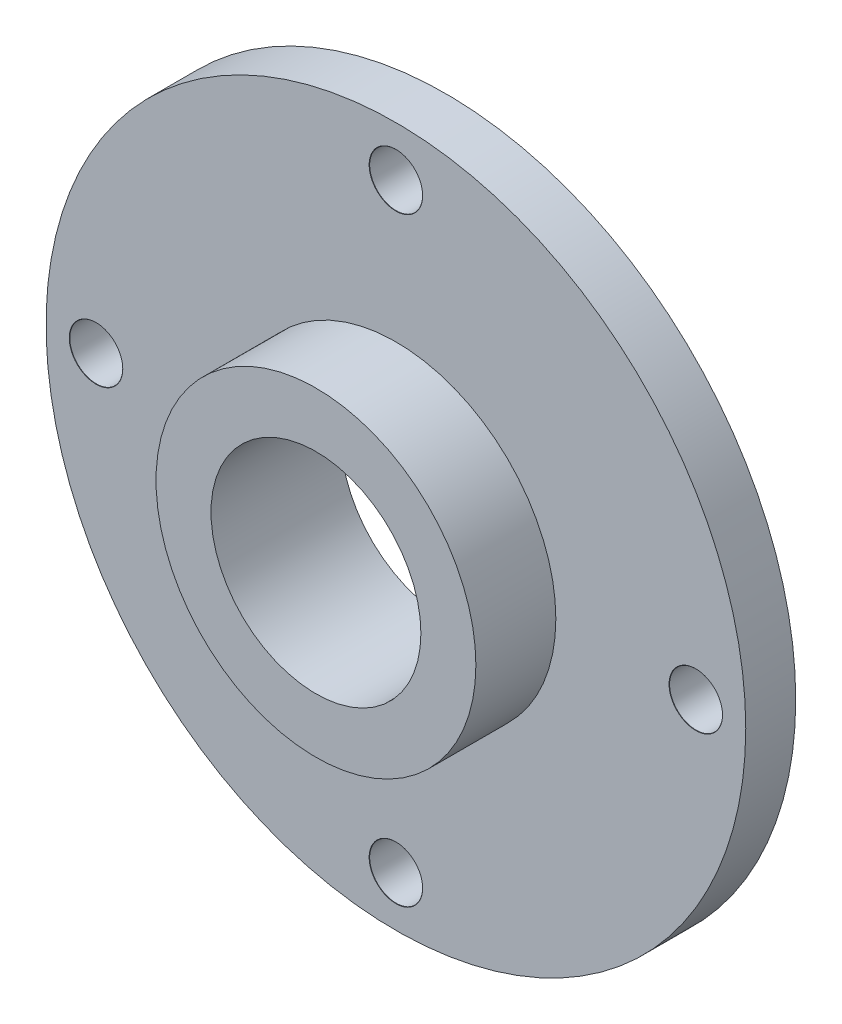
SolidWorks part; units mm, degrees
ref_plane "Front Plane" through (0, 0, 0) normal (0, 0, 1) x (1, 0, 0)
ref_plane "Top Plane" through (0, 0, 0) normal (0, 1, 0) x (1, 0, 0)
ref_plane "Right Plane" through (0, 0, 0) normal (1, 0, 0) x (0, 0, -1)
sketch "Sketch1" plane through (0, 0, 0) normal (0, 0, 1) x (1, 0, 0)
  circle A0 centre (0, 0) radius 35
  circle A1 centre (0, 0) radius 10.5
  dimension "D1" = 70
  dimension "D2" = 21
extrude "Boss-Extrude1" add sketch "Sketch1" along normal blind 5
sketch "Sketch2" plane through (0, 0, 5) normal (0, 0, 1) x (1, 0, 0)
  point P0 (0, 30)
  dimension "D1" = 30
hole_wizard "M5 Clearance Hole1" positions "Sketch2" profile "Sketch3" hole size "M5" standard "ISO" end condition through all
sketch "Sketch3" plane through (0, 30, 5) normal (1, 0, 0) x (0, -1, 0)
  line L0 (0, 0) -> (0, 5)
  line L1 (0, 5) -> (2.65, 5)
  line L2 (2.65, 5) -> (2.65, 0.025)
  line L3 (2.65, 0.025) -> (2.675, 0)
  line L5 (2.675, 0) -> (0, 0)
  line L6 (-2.65, 0.025) -> (-2.675, 0) construction
  line L11 (0, -6.35) -> (0, 107.95) construction
  dimension "Thru Hole Dia." = 5.3
  dimension "Thru Hole Depth" = 5
  dimension "Near C'Sink Dia." = 5.35
  dimension "Near C'Sink Angle" = 90
pattern_circular "CirPattern1" count 4 over 360 about axis through (0, 0, 0) along (0, 0, 1) of "M5 Clearance Hole1"
sketch "Sketch5" plane through (0, 0, 5) normal (0, 0, 1) x (1, 0, 0)
  circle A0 centre (0, 0) radius 16
  circle A1 centre (0, 0) radius 10.5 construction
  circle A2 centre (0, 0) radius 10.5
  dimension "D1" = 32
extrude "Boss-Extrude2" add sketch "Sketch5" along normal blind 8
